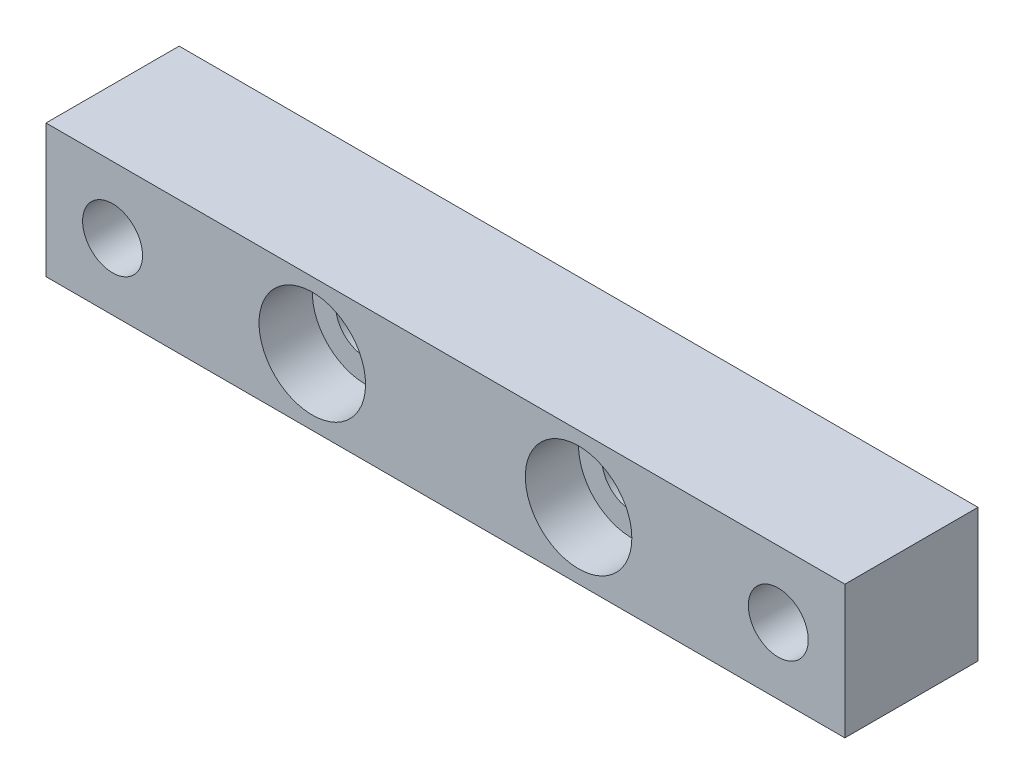
SolidWorks part; units mm, degrees
material "ABS"
ref_plane "Alzado" through (0, 0, 0) normal (0, 0, 1) x (1, 0, 0)
ref_plane "Planta" through (0, 0, 0) normal (0, 1, 0) x (1, 0, 0)
ref_plane "Vista lateral" through (0, 0, 0) normal (1, 0, 0) x (0, 0, -1)
sketch "Croquis1" plane through (0, 0, 0) normal (0, 0, 1) x (1, 0, 0)
  line L0 (10, 0) -> (-10, 0) construction
  line L1 (-10, 0) -> (-25, 0) construction
  line L2 (30, -5) -> (-30, -5)
  line L3 (30, -5) -> (30, 5)
  line L4 (30, 5) -> (-30, 5)
  line L5 (-30, -5) -> (-30, 5)
  line L6 (30, -5) -> (-30, 5) construction
  line L7 (30, 5) -> (-30, -5) construction
  line L8 (0, -5.5) -> (0, 5.5) construction
  circle A0 centre (-10, 0) radius 2.25
  circle A1 centre (10, 0) radius 2.25
  circle A4 centre (-25, 0) radius 2.25
  circle A5 centre (25, 0) radius 2.25
  point P4 (0, 0)
  point P7 (0, 0)
  dimension "D2" = 4.5
  dimension "D5" = 5
  dimension "D1" = 20
  dimension "D3" = 15
  dimension "D4" = 10
extrude "Saliente-Extruir1" add sketch "Croquis1" along normal mid plane 10
sketch "Croquis4" plane through (0, 0, 5) normal (0, 0, 1) x (1, 0, 0)
  circle A0 centre (-10, 0) radius 4
  circle A1 centre (10, 0) radius 4
  dimension "D1" = 8
extrude "Cortar-Extruir1" cut sketch "Croquis4" against normal blind 4
